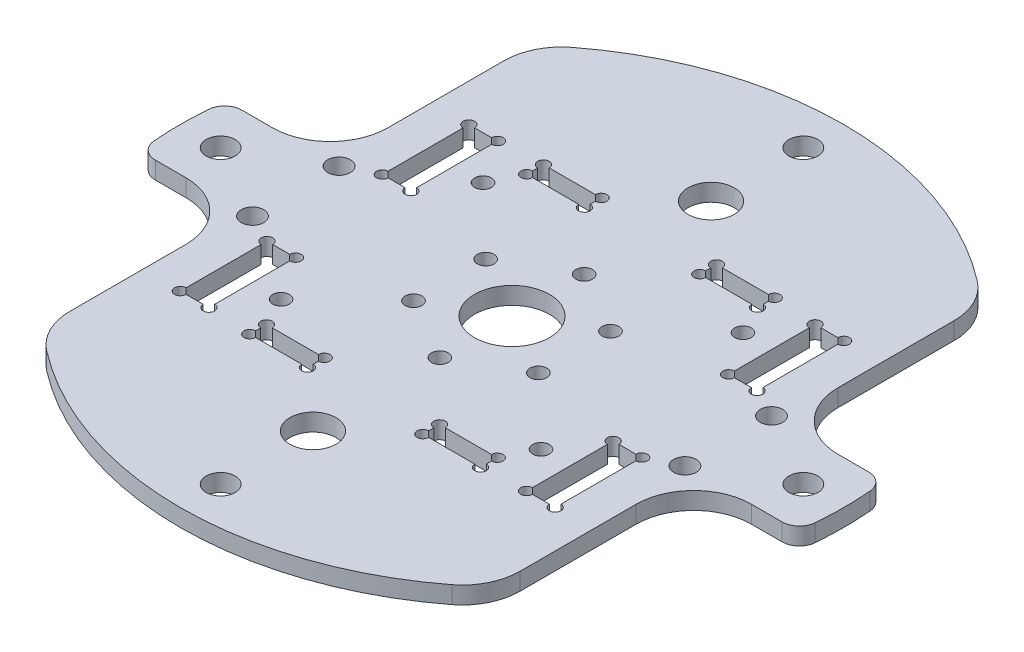
SolidWorks part; units mm, degrees
material "Thornel Mat VMA"
ref_plane "前视基准面" through (0, 0, 0) normal (0, 0, 1) x (1, 0, 0)
ref_plane "上视基准面" through (0, 0, 0) normal (0, 1, 0) x (1, 0, 0)
ref_plane "右视基准面" through (0, 0, 0) normal (1, 0, 0) x (0, 0, -1)
other "Configuration Table"
sketch "草图1" plane through (0, 0, 0) normal (0, 1, 0) x (1, 0, 0)
  circle A0 centre (0, 0) radius 57.5
  circle A1 centre (0, 0) radius 50.5 construction
  circle A2 centre (0, 50.5) radius 2.5
  circle A3 centre (35.7089, 35.7089) radius 2.5 construction
  circle A4 centre (50.5, 0) radius 2.5
  circle A5 centre (35.7089, -35.7089) radius 2.5 construction
  circle A6 centre (0, -50.5) radius 2.5
  circle A7 centre (-35.7089, -35.7089) radius 2.5 construction
  circle A8 centre (-50.5, 0) radius 2.5
  circle A9 centre (-35.7089, 35.7089) radius 2.5 construction
  dimension "D1" = 115
  dimension "D2" = 101
  dimension "D4" = 5
  dimension "D3" = 8
extrude "凸台-拉伸1" add sketch "草图1" along normal blind 3
sketch "草图2" plane through (0, 3, 0) normal (0, 1, 0) x (1, 0, 0)
  circle A0 centre (0, 0) radius 12.5 construction
  circle A1 centre (0, 12.5) radius 1.45
  circle A2 centre (10.8253, 6.25) radius 1.45
  circle A3 centre (10.8253, -6.25) radius 1.45
  circle A4 centre (0, -12.5) radius 1.45
  circle A5 centre (-10.8253, -6.25) radius 1.45
  circle A6 centre (-10.8253, 6.25) radius 1.45
  dimension "D1" = 25
  dimension "D2" = 2.9
  dimension "D3" = 6
extrude "切除-拉伸1" cut sketch "草图2" against normal through all
sketch "草图3" plane through (0, 3, 0) normal (0, 1, 0) x (1, 0, 0)
  line L0 (0, 0) -> (30, 0) construction
  line L1 (30, -17.5) -> (30, 17.5) construction
  line L2 (0, 0) -> (0, 57.5) construction
  line L3 (27.525, 10) -> (32.475, 10)
  line L4 (27.525, 10) -> (27.525, 25)
  line L5 (27.525, 25) -> (32.475, 25)
  line L6 (32.475, 10) -> (32.475, 25)
  line L7 (27.525, 10) -> (32.475, 25) construction
  line L8 (27.525, 25) -> (32.475, 10) construction
  line L9 (27.525, -10) -> (32.475, -10)
  line L10 (27.525, -10) -> (27.525, -25)
  line L11 (27.525, -25) -> (32.475, -25)
  line L12 (32.475, -10) -> (32.475, -25)
  line L13 (27.525, -10) -> (32.475, -25) construction
  line L14 (27.525, -25) -> (32.475, -10) construction
  line L15 (30, 17.5) -> (22.525, 17.5) construction
  line L16 (30, -17.5) -> (22.525, -17.5) construction
  line L17 (22.525, 17.5) -> (22.525, -17.5) construction
  line L18 (22.525, -7.5) -> (22.525, 7.5) construction
  line L19 (-22.525, -7.5) -> (-22.525, 7.5) construction
  line L20 (-22.525, 17.5) -> (-22.525, -17.5) construction
  line L21 (-30, -17.5) -> (-22.525, -17.5) construction
  line L22 (-30, 17.5) -> (-22.525, 17.5) construction
  line L23 (-27.525, -25) -> (-32.475, -10) construction
  line L24 (-27.525, -10) -> (-32.475, -25) construction
  line L25 (-27.525, 25) -> (-32.475, 10) construction
  line L26 (-27.525, 10) -> (-32.475, 25) construction
  line L27 (-30, -17.5) -> (-30, 17.5) construction
  line L28 (-32.475, -10) -> (-32.475, -25)
  line L29 (-27.525, -25) -> (-32.475, -25)
  line L30 (-27.525, -10) -> (-27.525, -25)
  line L31 (-27.525, -10) -> (-32.475, -10)
  line L32 (-32.475, 10) -> (-32.475, 25)
  line L33 (-27.525, 25) -> (-32.475, 25)
  line L34 (-27.525, 10) -> (-27.525, 25)
  line L35 (-27.525, 10) -> (-32.475, 10)
  line L36 (22.525, 7.5) -> (37.475, 7.5) construction
  line L37 (22.525, -7.5) -> (37.475, -7.5) construction
  circle A1 centre (0, 0) radius 57.5 construction
  circle A2 centre (22.525, 17.5) radius 1.45
  circle A3 centre (22.525, -17.5) radius 1.45
  circle A4 centre (22.525, 7.5) radius 1.95 construction
  circle A5 centre (22.525, -7.5) radius 1.95 construction
  circle A6 centre (-22.525, -7.5) radius 1.95 construction
  circle A7 centre (-22.525, 7.5) radius 1.95 construction
  circle A8 centre (-22.525, -17.5) radius 1.45
  circle A9 centre (-22.525, 17.5) radius 1.45
  circle A10 centre (37.475, 7.5) radius 1.95
  circle A11 centre (37.475, -7.5) radius 1.95
  circle A12 centre (-37.475, -7.5) radius 1.95
  circle A13 centre (-37.475, 7.5) radius 1.95
  point P6 (30, 0)
  point P25 (22.525, 0)
  point P45 (-22.525, 0)
  point P46 (-30, 0)
  dimension "D5" = 5
  dimension "D6" = 2.9
  dimension "D9" = 3.9
  dimension "D1" = 15
  dimension "D2" = 4.95
  dimension "D3" = 20
  dimension "D4" = 30
  dimension "D7" = 5
  dimension "D8" = 15
  dimension "D10" = 5
extrude "切除-拉伸2" cut sketch "草图3" against normal through all
sketch "草图4" plane through (0, 3, 0) normal (0, 1, 0) x (1, 0, 0)
  circle A0 centre (-32.475, 25) radius 1
  circle A1 centre (-27.525, 25) radius 1
  circle A2 centre (-27.525, 10) radius 1
  circle A3 centre (-32.475, 10) radius 1
  circle A4 centre (27.525, 25) radius 1
  circle A5 centre (32.475, 25) radius 1
  circle A6 centre (32.475, 10) radius 1
  circle A7 centre (27.525, 10) radius 1
  circle A8 centre (27.525, -10) radius 1
  circle A9 centre (32.475, -10) radius 1
  circle A10 centre (32.475, -25) radius 1
  circle A11 centre (27.525, -25) radius 1
  circle A12 centre (-27.525, -25) radius 1
  circle A13 centre (-32.475, -25) radius 1
  circle A14 centre (-32.475, -10) radius 1
  circle A15 centre (-27.525, -10) radius 1
  dimension "D1" = 2
extrude "切除-拉伸3" cut sketch "草图4" against normal through all
sketch "草图5" plane through (0, 3, 0) normal (0, 1, 0) x (1, 0, 0)
  line L0 (0, 0) -> (0, -25.45) construction
  line L1 (-20, -25.45) -> (20, -25.45) construction
  line L2 (20, -24) -> (10, -24) construction
  line L3 (20, -25.45) -> (10, -25.45)
  line L4 (20, -25.45) -> (20, -22.55)
  line L5 (20, -22.55) -> (10, -22.55)
  line L6 (10, -25.45) -> (10, -22.55)
  line L7 (-20, -24) -> (-10, -24) construction
  line L8 (-10, -25.45) -> (-10, -22.55)
  line L9 (-20, -22.55) -> (-10, -22.55)
  line L10 (-20, -25.45) -> (-20, -22.55)
  line L11 (-20, -25.45) -> (-10, -25.45)
  line L12 (0, 0) -> (57.5, 0) construction
  line L13 (-20, 24) -> (-10, 24) construction
  line L14 (20, 24) -> (10, 24) construction
  line L15 (-20, 25.45) -> (20, 25.45) construction
  line L16 (-20, 25.45) -> (-10, 25.45)
  line L17 (-20, 25.45) -> (-20, 22.55)
  line L18 (-20, 22.55) -> (-10, 22.55)
  line L19 (-10, 25.45) -> (-10, 22.55)
  line L20 (10, 25.45) -> (10, 22.55)
  line L21 (20, 22.55) -> (10, 22.55)
  line L22 (20, 25.45) -> (20, 22.55)
  line L23 (20, 25.45) -> (10, 25.45)
  circle A1 centre (22.525, -17.5) radius 1.45 construction
  circle A2 centre (0, 0) radius 57.5 construction
  point P6 (0, -25.45)
  point P34 (0, 25.45)
  dimension "D1" = 10
  dimension "D2" = 2.9
  dimension "D3" = 6.5
  dimension "D4" = 20
extrude "切除-拉伸4" cut sketch "草图5" against normal through all
sketch "草图6" plane through (0, 3, 0) normal (0, 1, 0) x (1, 0, 0)
  line L0 (-10, 22.55) -> (-10, 25.45) construction
  line L1 (-10, 25.45) -> (-20, 25.45) construction
  circle A0 centre (-20, 25.45) radius 1
  circle A1 centre (-10, 25.45) radius 1
  circle A2 centre (-10, 22.55) radius 1
  circle A3 centre (-20, 22.55) radius 1
  circle A4 centre (10, 22.55) radius 1
  circle A5 centre (10, 25.45) radius 1
  circle A6 centre (20, 25.45) radius 1
  circle A7 centre (20, 22.55) radius 1
  circle A8 centre (20, -22.55) radius 1
  circle A9 centre (20, -25.45) radius 1
  circle A10 centre (10, -25.45) radius 1
  circle A11 centre (10, -22.55) radius 1
  circle A12 centre (-10, -22.55) radius 1
  circle A13 centre (-10, -25.45) radius 1
  circle A14 centre (-20, -25.45) radius 1
  circle A15 centre (-20, -22.55) radius 1
  dimension "D1" = 2
extrude "切除-拉伸5" cut sketch "草图6" against normal through all
sketch "草图7" plane through (0, 3, 0) normal (0, 1, 0) x (1, 0, 0)
  circle A0 centre (0, 0) radius 34.5 construction
  circle A1 centre (0, 34.5) radius 4
  circle A2 centre (34.5, 0) radius 4 construction
  circle A3 centre (0, -34.5) radius 4
  circle A4 centre (-34.5, 0) radius 4 construction
  dimension "D1" = 69
  dimension "D2" = 8
  dimension "D3" = 4
extrude "切除-拉伸6" cut sketch "草图7" against normal through all
sketch "草图8" plane through (0, 3, 0) normal (0, 1, 0) x (1, 0, 0)
  circle A0 centre (0, 0) radius 6.5
  dimension "D1" = 13
extrude "切除-拉伸7" cut sketch "草图8" against normal through all
sketch "草图9" plane through (0, 3, 0) normal (0, 1, 0) x (1, 0, 0)
  line L0 (-39.0088, 14) -> (-39.0088, 30.2667) construction
  line L1 (-39.0088, 30.2667) -> (-18.7686, 30.2667) construction
  line L2 (-18.7686, 30.2667) -> (-7.5, 39.7222) construction
  line L3 (-7.5, 39.7222) -> (-7.5, 57.0088) construction
  line L4 (-39.0088, 14) -> (-44.0088, 14) construction
  line L5 (-44.0088, 14) -> (-44.0088, 7.5) construction
  line L6 (-44.0088, 7.5) -> (-57.0088, 7.5) construction
  line L7 (0, 0) -> (0, 57.5) construction
  line L8 (44.0088, 7.5) -> (57.0088, 7.5) construction
  line L9 (44.0088, 14) -> (44.0088, 7.5) construction
  line L10 (39.0088, 14) -> (44.0088, 14) construction
  line L11 (7.5, 39.7222) -> (7.5, 57.0088) construction
  line L12 (18.7686, 30.2667) -> (7.5, 39.7222) construction
  line L13 (39.0088, 30.2667) -> (18.7686, 30.2667) construction
  line L14 (39.0088, 14) -> (39.0088, 30.2667) construction
  line L15 (0, 0) -> (-57.5, 0) construction
  line L16 (39.0088, -14) -> (39.0088, -30.2667) construction
  line L17 (39.0088, -30.2667) -> (18.7686, -30.2667) construction
  line L18 (18.7686, -30.2667) -> (7.5, -39.7222) construction
  line L19 (7.5, -39.7222) -> (7.5, -57.0088) construction
  line L20 (39.0088, -14) -> (44.0088, -14) construction
  line L21 (44.0088, -14) -> (44.0088, -7.5) construction
  line L22 (44.0088, -7.5) -> (57.0088, -7.5) construction
  line L23 (-44.0088, -7.5) -> (-57.0088, -7.5) construction
  line L24 (-44.0088, -14) -> (-44.0088, -7.5) construction
  line L25 (-39.0088, -14) -> (-44.0088, -14) construction
  line L26 (-7.5, -39.7222) -> (-7.5, -57.0088) construction
  line L27 (-18.7686, -30.2667) -> (-7.5, -39.7222) construction
  line L28 (-39.0088, -30.2667) -> (-18.7686, -30.2667) construction
  line L29 (-39.0088, -14) -> (-39.0088, -30.2667) construction
  line L30 (-39.0088, 14) -> (-39.0088, 7.5) construction
  line L31 (-39.0088, 7.5) -> (-44.0088, 7.5) construction
  line L32 (39.0088, 7.5) -> (44.0088, 7.5) construction
  line L33 (39.0088, 14) -> (39.0088, 7.5) construction
  line L34 (-39.0088, -7.5) -> (-44.0088, -7.5) construction
  line L35 (-39.0088, -14) -> (-39.0088, -7.5) construction
  line L36 (39.0088, -7.5) -> (44.0088, -7.5) construction
  line L37 (39.0088, -14) -> (39.0088, -7.5) construction
  line L38 (-39.0088, 30.2667) -> (-39.0088, 17.5)
  line L39 (-49.0088, 7.5) -> (-57.0088, 7.5)
  line L40 (-57.0088, -7.5) -> (-49.0088, -7.5)
  line L41 (-39.0088, -17.5) -> (-39.0088, -30.2667)
  line L42 (39.0088, -30.2667) -> (39.0088, -17.5)
  line L43 (49.0088, -7.5) -> (57.0088, -7.5)
  line L44 (57.0088, 7.5) -> (49.0088, 7.5)
  line L45 (39.0088, 17.5) -> (39.0088, 30.2667)
  line L46 (-7.5, 39.7222) -> (-39.0088, 39.7222) construction
  line L47 (-39.0088, 39.7222) -> (-39.0088, 30.2667)
  line L48 (39.0088, 39.7222) -> (39.0088, 30.2667)
  line L49 (7.5, 39.7222) -> (39.0088, 39.7222) construction
  line L50 (-39.0088, -39.7222) -> (-39.0088, -30.2667)
  line L51 (-7.5, -39.7222) -> (-39.0088, -39.7222) construction
  line L52 (39.0088, -39.7222) -> (39.0088, -30.2667)
  line L53 (7.5, -39.7222) -> (39.0088, -39.7222) construction
  line L54 (-39.0088, 39.7222) -> (-39.0088, 42.2441)
  line L55 (39.0088, 39.7222) -> (39.0088, 42.2441)
  line L56 (39.0088, -39.7222) -> (39.0088, -42.2441)
  line L57 (-39.0088, -39.7222) -> (-39.0088, -42.2441)
  circle A0 centre (0, 0) radius 57.5 construction
  arc A1 (-57.0088, 7.5) -> (-7.5, 57.0088) centre (0, 0) cw construction
  arc A2 (57.0088, 7.5) -> (7.5, 57.0088) centre (0, 0) ccw construction
  arc A3 (57.0088, -7.5) -> (7.5, -57.0088) centre (0, 0) cw construction
  arc A4 (-57.0088, -7.5) -> (-7.5, -57.0088) centre (0, 0) ccw construction
  arc A5 (-39.0088, 17.5) -> (-49.0088, 7.5) centre (-49.0088, 17.5) cw
  arc A6 (-49.0088, -7.5) -> (-39.0088, -17.5) centre (-49.0088, -17.5) cw
  arc A7 (39.0088, -17.5) -> (49.0088, -7.5) centre (49.0088, -17.5) cw
  arc A8 (49.0088, 7.5) -> (39.0088, 17.5) centre (49.0088, 17.5) cw
  arc A9 (-39.0088, 42.2441) -> (-57.0088, 7.5) centre (0, 0) ccw
  arc A10 (39.0088, 42.2441) -> (57.0088, 7.5) centre (0, 0) cw
  arc A11 (39.0088, -42.2441) -> (57.0088, -7.5) centre (0, 0) ccw
  arc A12 (-39.0088, -42.2441) -> (-57.0088, -7.5) centre (0, 0) cw
  dimension "D7" = 10
  dimension "D8" = 10
  dimension "D1" = 15
  dimension "D2" = 6.5
  dimension "D3" = 5
  dimension "D4" = 13
  dimension "D5" = 15
  dimension "D6" = 40
extrude "切除-拉伸8" cut sketch "草图9" against normal through all
fillet "圆角1" radius 10 4 edges at (-39.0088, 1.5, 42.2441) (-39.0088, 1.5, -42.2441) (39.0088, 1.5, 42.2441) (39.0088, 1.5, -42.2441)
fillet "圆角2" radius 3 4 edges at (57.0088, 1.5, 7.5) (57.0088, 1.5, -7.5) (-57.0088, 1.5, -7.5) (-57.0088, 1.5, 7.5)
